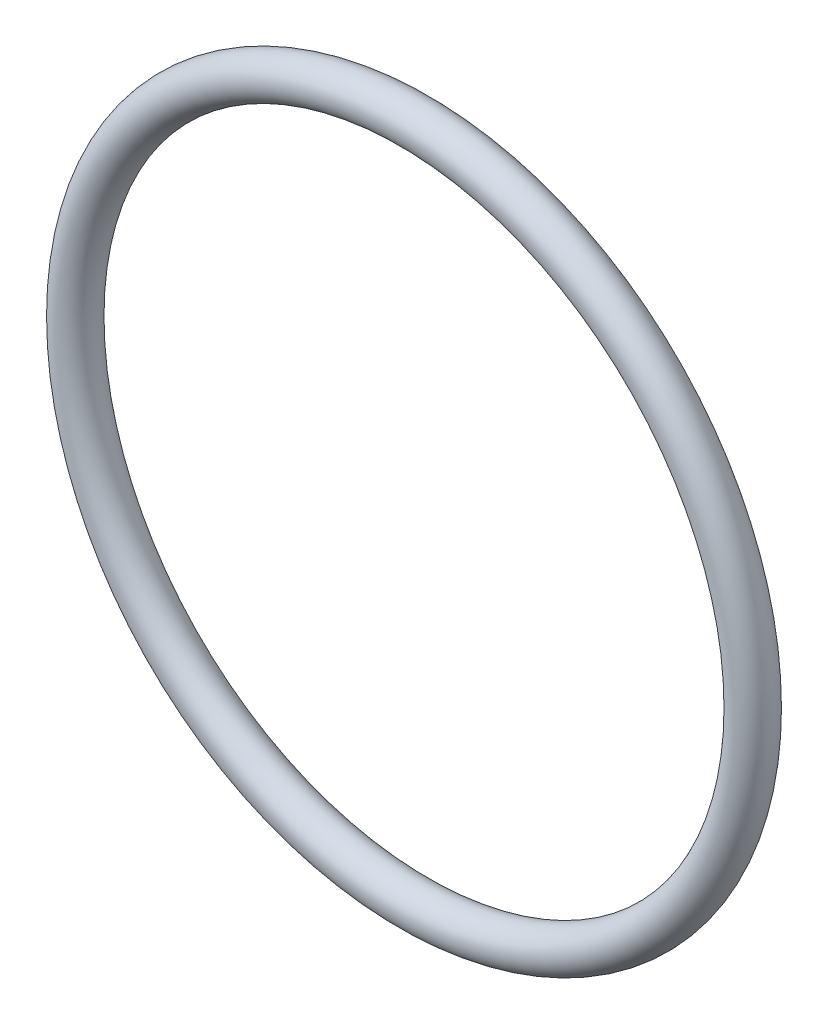
SolidWorks part; units mm, degrees
ref_plane "Front Plane" through (0, 0, 0) normal (0, 0, 1) x (1, 0, 0)
ref_plane "Top Plane" through (0, 0, 0) normal (0, 1, 0) x (1, 0, 0)
ref_plane "Right Plane" through (0, 0, 0) normal (1, 0, 0) x (0, 0, -1)
sketch "Sketch1" plane through (0, 0, 0) normal (0, 0, 1) x (1, 0, 0)
  circle A4 centre (0, 0) radius 25
  dimension "tube_width" = 50
sketch "Sketch2" plane through (0, 0, 0) normal (0, 1, 0) x (1, 0, 0)
  circle A0 centre (-25, 0) radius 1.5
  dimension "bead_diameter" = 3
  dimension "D1" = 25
sweep "Sweep1" add profiles "Sketch2" path "Sketch1"
equation "\"D1@Sketch2\"=\"tube_width@Sketch1\"/2"
